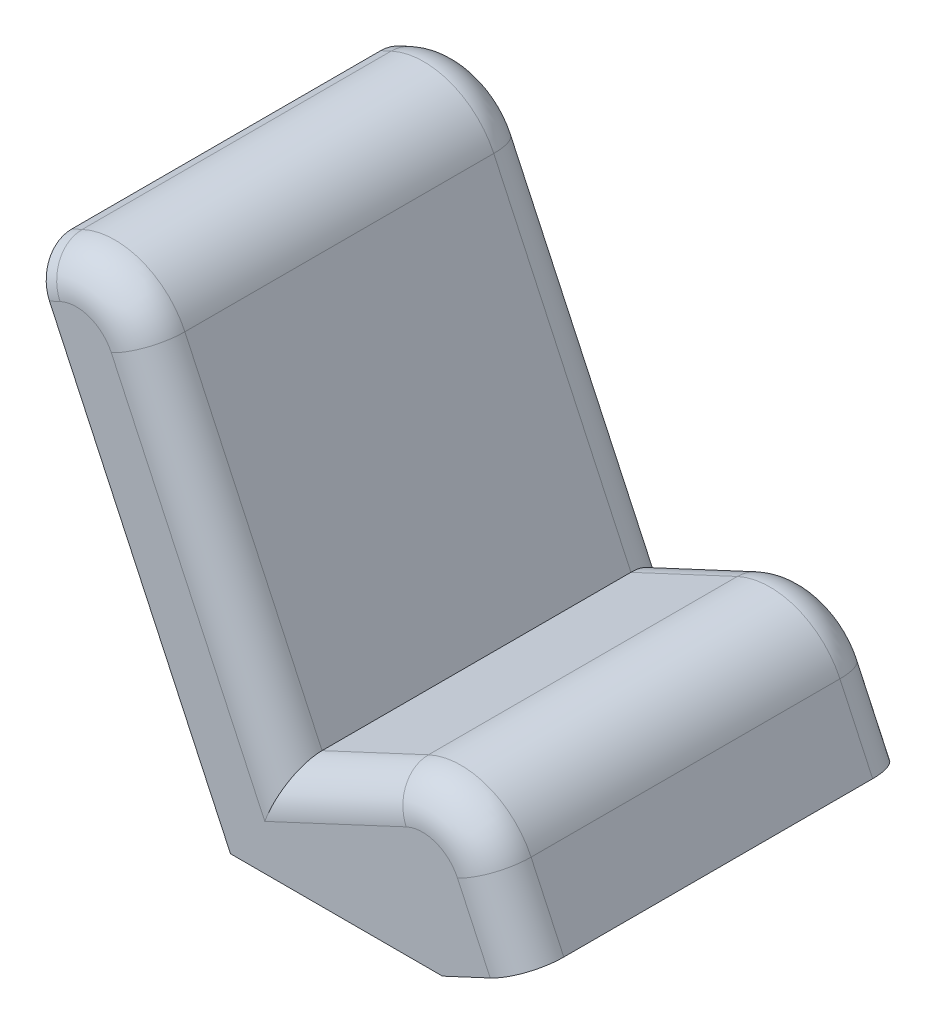
SolidWorks part; units mm, degrees
ref_plane "Front Plane" through (0, 0, 0) normal (0, 0, 1) x (1, 0, 0)
ref_plane "Top Plane" through (0, 0, 0) normal (0, 1, 0) x (1, 0, 0)
ref_plane "Right Plane" through (0, 0, 0) normal (1, 0, 0) x (0, 0, -1)
sketch "Sketch3" plane through (0, 0, 0) normal (0, 0, 1) x (1, 0, 0)
  line L0 (-50.7142, 108.7569) -> (0, 0)
  line L1 (0, 0) -> (57.1, 0)
  line L2 (57.1, 0) -> (78.5451, 10)
  line L3 (78.5451, 10) -> (70.0681, 28.179)
  line L4 (43.4896, 37.8527) -> (15.9268, 25)
  line L5 (15.9268, 25) -> (-19.6041, 101.1962)
  line L6 (-46.1827, 110.87) -> (-50.7142, 108.7569)
  arc A0 (70.0681, 28.179) -> (43.4896, 37.8527) centre (51.9419, 19.7266) ccw
  arc A1 (-19.6041, 101.1962) -> (-46.1827, 110.87) centre (-37.7303, 92.7439) ccw
  point P12 (-28.0565, 119.3224)
  dimension "D5" = 20
  dimension "D9" = 20
  dimension "D1" = 120
  dimension "D2" = 57.1
  dimension "D3" = 10
  dimension "D4" = 25
  dimension "D6" = 25
  dimension "D7" = 25
  dimension "D8" = 50.4122
extrude "Boss-Extrude1" add sketch "Sketch3" along normal mid plane 100
sketch "Sketch4" plane through (0, 0, 0) normal (0, -1, 0) x (1, 0, 0)
  line L0 (0, 50) -> (0, -50) construction
  circle A0 centre (30, 0) radius 7.5
  dimension "D1" = 15
  dimension "D2" = 30
extrude "Boss-Extrude2" add sketch "Sketch4" along normal blind 10
fillet "Fillet1" radius 10 12 edges at (74.3066, 19.0895, -50) (29.7082, 31.4264, -50) (74.3066, 19.0895, 50) (29.7082, 31.4264, 50) (-48.4484, 109.8135, -50) (-30.8899, 111.5377, -50) (-48.4484, 109.8135, 50) (-30.8899, 111.5377, 50) (58.7823, 38.5204, -50) (58.7823, 38.5204, 50) (-1.8387, 63.0981, -50) (-1.8387, 63.0981, 50)
chamfer "Chamfer1" distance 2 angle 45 5 edges at (-23.244, 49.8469, 50) (-23.244, 49.8469, -50) (-49.4764, 106.1024, 47.0711) (-49.4764, 106.1024, -47.0711) (-50.7142, 108.7569, 0)
